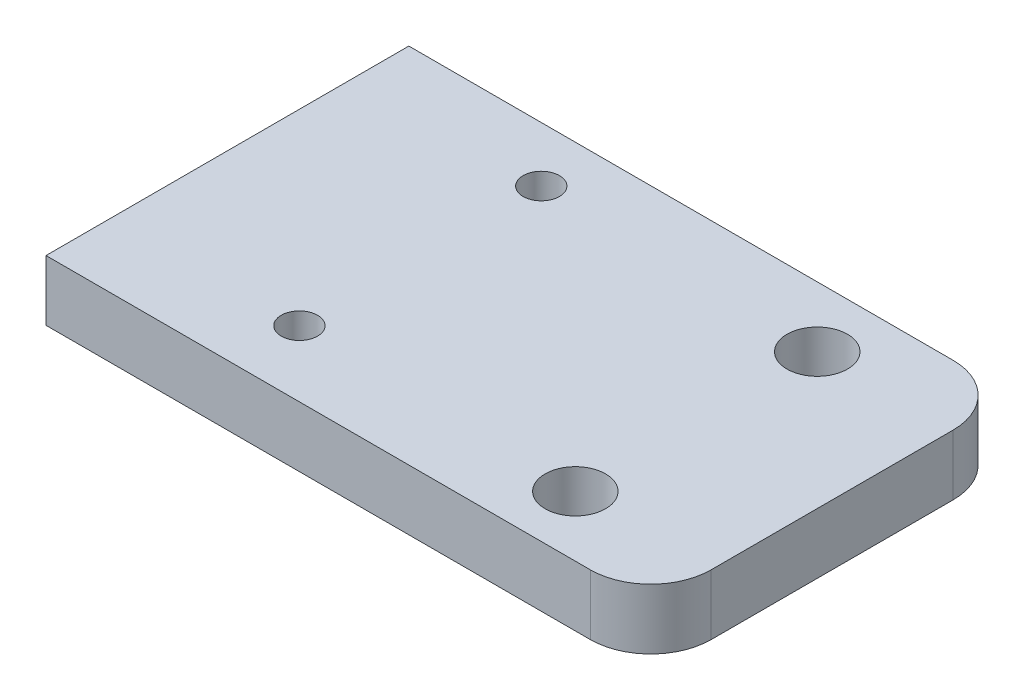
SolidWorks part; units mm, degrees
ref_plane "Front Plane" through (0, 0, 0) normal (0, 0, 1) x (1, 0, 0)
ref_plane "Top Plane" through (0, 0, 0) normal (0, 1, 0) x (1, 0, 0)
ref_plane "Right Plane" through (0, 0, 0) normal (1, 0, 0) x (0, 0, -1)
sketch "Sketch1" plane through (0, 0, 0) normal (0, 1, 0) x (1, 0, 0)
  line L0 (-34.5, 5.45) -> (-34.5, 25.45) construction
  line L1 (0, 0) -> (-50, 0)
  line L2 (0, 0) -> (0, 30)
  line L3 (0, 30) -> (-50, 30)
  line L4 (-50, 0) -> (-50, 30)
  circle A0 centre (-34.5, 5.45) radius 1.5
  circle A1 centre (-34.5, 25.45) radius 1.5
  dimension "D5" = 3
  dimension "D6" = 3
  dimension "D7" = 5.45
  dimension "D1" = 50
  dimension "D2" = 30
  dimension "D3" = 15.5
  dimension "D4" = 20
extrude "Boss-Extrude1" add sketch "Sketch1" along normal blind 5
fillet "Fillet1" radius 5 2 edges at (0, 2.5, -30) (0, 2.5, 0)
sketch "Sketch2" plane through (0, 0, 0) normal (0, -1, 0) x (1, 0, 0)
  line L0 (-9.2279, 2.6384) -> (-11.2326, 2.6384) construction
  line L1 (-11.2326, 2.6384) -> (-11.2326, -30) construction
  line L2 (-5, -30) -> (-50, -30) construction
  line L3 (0, -5) -> (0, -25) construction
  line L4 (-50, 0) -> (-5, 0) construction
  circle A0 centre (-11.2326, -5) radius 2.5
  circle A1 centre (-11.2326, -25) radius 2.5
  dimension "D1" = 5
  dimension "D3" = 5
  dimension "D4" = 20
  dimension "D2" = 11.2326
extrude "Cut-Extrude1" cut sketch "Sketch2" against normal blind 9
